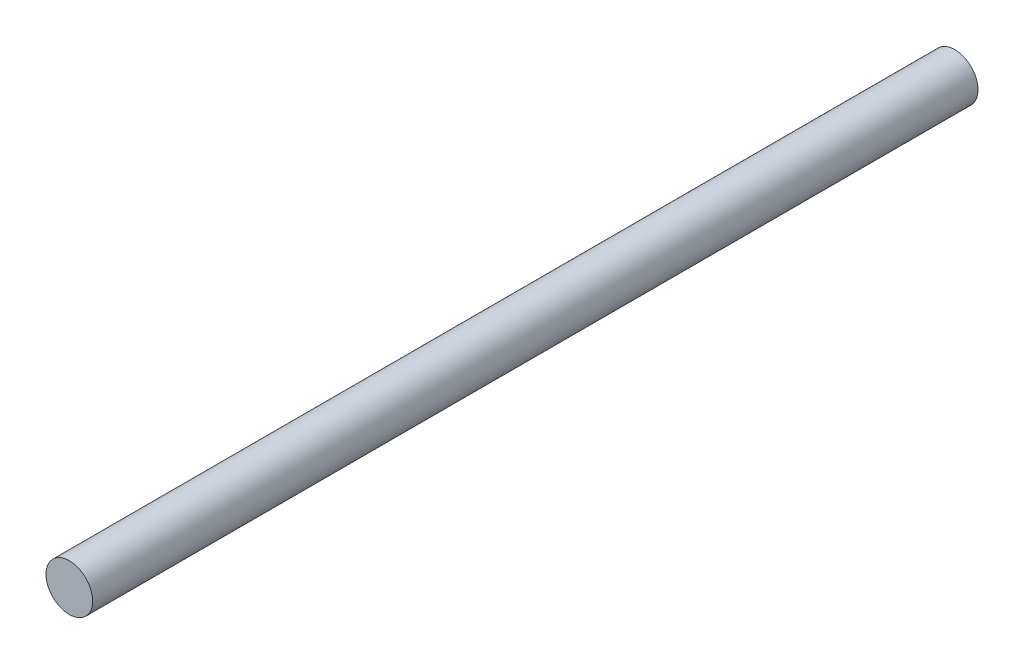
SolidWorks part; units mm, degrees
material "1060 Alloy"
ref_plane "Front Plane" through (0, 0, 0) normal (0, 0, 1) x (1, 0, 0)
ref_plane "Top Plane" through (0, 0, 0) normal (0, 1, 0) x (1, 0, 0)
ref_plane "Right Plane" through (0, 0, 0) normal (1, 0, 0) x (0, 0, -1)
sketch "Sketch1" plane through (0, 0, 0) normal (0, 0, 1) x (1, 0, 0)
  circle A1 centre (0, 0) radius 8.0266
  point P3 (0, 0)
  point P5 (0, 0)
  dimension "D1" = 16.0531
extrude "Boss-Extrude1" add sketch "Sketch1" along normal blind 304.8 contours A1
